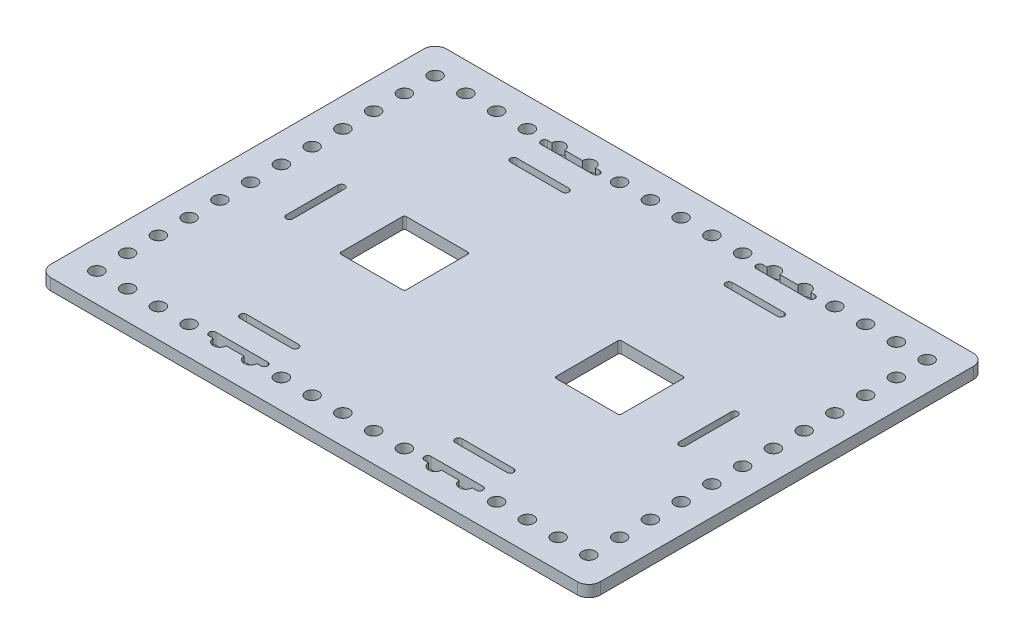
SolidWorks part; units mm, degrees
ref_plane "Front Plane" through (0, 0, 0) normal (0, 0, 1) x (1, 0, 0)
ref_plane "Top Plane" through (0, 0, 0) normal (0, 1, 0) x (1, 0, 0)
ref_plane "Right Plane" through (0, 0, 0) normal (1, 0, 0) x (0, 0, -1)
ref_plane "Plane1" through (0, 3, 0) normal (0, 1, 0) x (1, 0, 0)
sketch "Sketch1" plane through (0, 3, 0) normal (0, 1, 0) x (1, 0, 0)
  line L0 (71.5, -48.5) -> (71.5, 48.5)
  line L1 (68.5, 51.5) -> (-68.5, 51.5)
  line L2 (-71.5, 48.5) -> (-71.5, -48.5)
  line L3 (-68.5, -51.5) -> (68.5, -51.5)
  line L4 (21.25, 44.05) -> (22.3007, 44.05)
  line L5 (25.6993, 44.05) -> (30.3007, 44.05)
  line L6 (33.6993, 44.05) -> (34.75, 44.05)
  line L7 (34.75, 42.3) -> (21.25, 42.3)
  line L8 (22.3007, -44.05) -> (21.25, -44.05)
  line L9 (21.25, -42.3) -> (34.75, -42.3)
  line L10 (34.75, -44.05) -> (33.6993, -44.05)
  line L11 (30.3007, -44.05) -> (25.6993, -44.05)
  line L12 (21.25, 36.05) -> (34.75, 36.05)
  line L13 (34.75, 34.3) -> (21.25, 34.3)
  line L14 (50.25, -6.75) -> (50.25, 6.75)
  line L15 (52, 6.75) -> (52, -6.75)
  line L16 (21.25, -34.3) -> (34.75, -34.3)
  line L17 (34.75, -36.05) -> (21.25, -36.05)
  line L18 (36, -8.5) -> (20, -8.5)
  line L19 (19.5, -8) -> (19.5, 8)
  line L20 (20, 8.5) -> (36, 8.5)
  line L21 (36.5, 8) -> (36.5, -8)
  line L22 (-21.25, 34.3) -> (-34.75, 34.3)
  line L23 (-34.75, 36.05) -> (-21.25, 36.05)
  line L24 (-50.25, 6.75) -> (-50.25, -6.75)
  line L25 (-52, -6.75) -> (-52, 6.75)
  line L26 (-21.25, -36.05) -> (-34.75, -36.05)
  line L27 (-34.75, -34.3) -> (-21.25, -34.3)
  line L28 (-19.5, 8) -> (-19.5, -8)
  line L29 (-20, -8.5) -> (-36, -8.5)
  line L30 (-36.5, -8) -> (-36.5, 8)
  line L31 (-36, 8.5) -> (-20, 8.5)
  line L32 (-34.75, -42.3) -> (-21.25, -42.3)
  line L33 (-21.25, -44.05) -> (-22.3007, -44.05)
  line L34 (-25.6993, -44.05) -> (-30.3007, -44.05)
  line L35 (-33.6993, -44.05) -> (-34.75, -44.05)
  line L36 (-34.75, 44.05) -> (-33.6993, 44.05)
  line L37 (-30.3007, 44.05) -> (-25.6993, 44.05)
  line L38 (-22.3007, 44.05) -> (-21.25, 44.05)
  line L39 (-21.25, 42.3) -> (-34.75, 42.3)
  arc A0 (68.5, -51.5) -> (71.5, -48.5) centre (68.5, -48.5) ccw
  arc A1 (71.5, 48.5) -> (68.5, 51.5) centre (68.5, 48.5) ccw
  arc A2 (-68.5, 51.5) -> (-71.5, 48.5) centre (-68.5, 48.5) ccw
  arc A3 (-71.5, -48.5) -> (-68.5, -51.5) centre (-68.5, -48.5) ccw
  arc A4 (22.3007, 44.05) -> (25.6993, 44.05) centre (24, 44) cw
  arc A5 (30.3007, 44.05) -> (33.6993, 44.05) centre (32, 44) cw
  arc A6 (34.75, 44.05) -> (34.75, 42.3) centre (34.75, 43.175) cw
  arc A7 (21.25, 42.3) -> (21.25, 44.05) centre (21.25, 43.175) cw
  arc A8 (21.25, -44.05) -> (21.25, -42.3) centre (21.25, -43.175) cw
  arc A9 (34.75, -42.3) -> (34.75, -44.05) centre (34.75, -43.175) cw
  arc A10 (33.6993, -44.05) -> (30.3007, -44.05) centre (32, -44) cw
  arc A11 (25.6993, -44.05) -> (22.3007, -44.05) centre (24, -44) cw
  arc A12 (34.75, 36.05) -> (34.75, 34.3) centre (34.75, 35.175) cw
  arc A13 (21.25, 34.3) -> (21.25, 36.05) centre (21.25, 35.175) cw
  arc A14 (52, -6.75) -> (50.25, -6.75) centre (51.125, -6.75) cw
  arc A15 (50.25, 6.75) -> (52, 6.75) centre (51.125, 6.75) cw
  arc A16 (34.75, -34.3) -> (34.75, -36.05) centre (34.75, -35.175) cw
  arc A17 (21.25, -36.05) -> (21.25, -34.3) centre (21.25, -35.175) cw
  arc A18 (36.5, -8) -> (36, -8.5) centre (36, -8) cw
  arc A19 (20, -8.5) -> (19.5, -8) centre (20, -8) cw
  arc A20 (19.5, 8) -> (20, 8.5) centre (20, 8) cw
  arc A21 (36, 8.5) -> (36.5, 8) centre (36, 8) cw
  circle A22 centre (-64, 44) radius 1.7
  circle A23 centre (-64, 28) radius 1.7
  circle A24 centre (-64, 12) radius 1.7
  circle A25 centre (-64, -4) radius 1.7
  circle A26 centre (-64, -20) radius 1.7
  circle A27 centre (-64, -36) radius 1.7
  circle A28 centre (56, -44) radius 1.7
  circle A29 centre (40, -44) radius 1.7
  circle A30 centre (8, -44) radius 1.7
  circle A31 centre (-8, -44) radius 1.7
  circle A32 centre (-40, -44) radius 1.7
  circle A33 centre (-56, -44) radius 1.7
  circle A34 centre (-64, -44) radius 1.7
  circle A35 centre (-48, -44) radius 1.7
  circle A36 centre (-16, -44) radius 1.7
  circle A37 centre (0, -44) radius 1.7
  circle A38 centre (16, -44) radius 1.7
  circle A39 centre (48, -44) radius 1.7
  circle A40 centre (64, -44) radius 1.7
  circle A41 centre (-64, -28) radius 1.7
  circle A42 centre (-64, -12) radius 1.7
  circle A43 centre (-64, 4) radius 1.7
  circle A44 centre (-64, 20) radius 1.7
  circle A45 centre (-64, 36) radius 1.7
  circle A46 centre (64, -20) radius 1.7
  circle A47 centre (64, -4) radius 1.7
  circle A48 centre (64, 12) radius 1.7
  circle A49 centre (64, 28) radius 1.7
  circle A50 centre (-48, 44) radius 1.7
  circle A51 centre (-16, 44) radius 1.7
  circle A52 centre (0, 44) radius 1.7
  circle A53 centre (16, 44) radius 1.7
  circle A54 centre (48, 44) radius 1.7
  circle A55 centre (64, 44) radius 1.7
  circle A56 centre (56, 44) radius 1.7
  circle A57 centre (40, 44) radius 1.7
  circle A58 centre (8, 44) radius 1.7
  circle A59 centre (-8, 44) radius 1.7
  circle A60 centre (-40, 44) radius 1.7
  circle A61 centre (-56, 44) radius 1.7
  circle A62 centre (64, 36) radius 1.7
  circle A63 centre (64, 20) radius 1.7
  circle A64 centre (64, 4) radius 1.7
  circle A65 centre (64, -12) radius 1.7
  circle A66 centre (64, -28) radius 1.7
  circle A67 centre (64, -36) radius 1.7
  arc A68 (-21.25, 36.05) -> (-21.25, 34.3) centre (-21.25, 35.175) cw
  arc A69 (-34.75, 34.3) -> (-34.75, 36.05) centre (-34.75, 35.175) cw
  arc A70 (-52, 6.75) -> (-50.25, 6.75) centre (-51.125, 6.75) cw
  arc A71 (-50.25, -6.75) -> (-52, -6.75) centre (-51.125, -6.75) cw
  arc A72 (-21.25, -34.3) -> (-21.25, -36.05) centre (-21.25, -35.175) cw
  arc A73 (-34.75, -36.05) -> (-34.75, -34.3) centre (-34.75, -35.175) cw
  arc A74 (-20, 8.5) -> (-19.5, 8) centre (-20, 8) cw
  arc A75 (-19.5, -8) -> (-20, -8.5) centre (-20, -8) cw
  arc A76 (-36, -8.5) -> (-36.5, -8) centre (-36, -8) cw
  arc A77 (-36.5, 8) -> (-36, 8.5) centre (-36, 8) cw
  arc A78 (-21.25, -42.3) -> (-21.25, -44.05) centre (-21.25, -43.175) cw
  arc A79 (-22.3007, -44.05) -> (-25.6993, -44.05) centre (-24, -44) cw
  arc A80 (-30.3007, -44.05) -> (-33.6993, -44.05) centre (-32, -44) cw
  arc A81 (-34.75, -44.05) -> (-34.75, -42.3) centre (-34.75, -43.175) cw
  arc A82 (-33.6993, 44.05) -> (-30.3007, 44.05) centre (-32, 44) cw
  arc A83 (-25.6993, 44.05) -> (-22.3007, 44.05) centre (-24, 44) cw
  arc A84 (-21.25, 44.05) -> (-21.25, 42.3) centre (-21.25, 43.175) cw
  arc A85 (-34.75, 42.3) -> (-34.75, 44.05) centre (-34.75, 43.175) cw
extrude "Boss-Extrude1" add sketch "Sketch1" against normal blind 3
